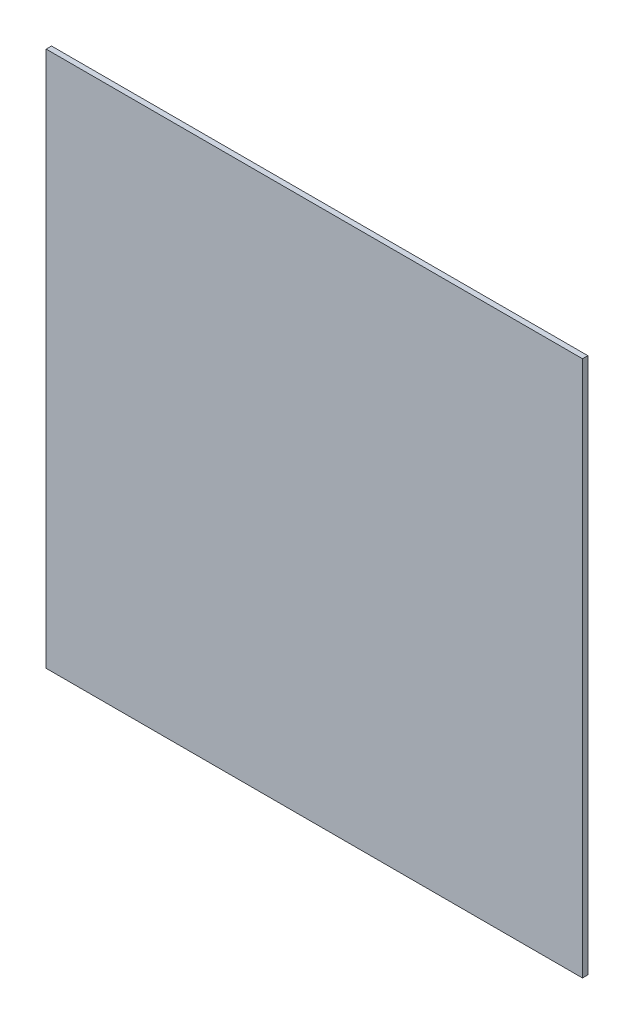
SolidWorks part; units mm, degrees
ref_plane "前视基准面" through (0, 0, 0) normal (0, 0, 1) x (1, 0, 0)
ref_plane "上视基准面" through (0, 0, 0) normal (0, 1, 0) x (1, 0, 0)
ref_plane "右视基准面" through (0, 0, 0) normal (1, 0, 0) x (0, 0, -1)
sketch "草图1" plane through (0, 0, 0) normal (0, 0, 1) x (1, 0, 0)
  line L1 (750, -750) -> (-750, -750)
  line L2 (750, -750) -> (750, 750)
  line L3 (750, 750) -> (-750, 750)
  line L4 (-750, -750) -> (-750, 750)
  line L5 (750, -750) -> (-750, 750) construction
  line L6 (750, 750) -> (-750, -750) construction
  point P0 (0, 0)
  dimension "D1" = 1500
  dimension "D2" = 1500
extrude "凸台-拉伸1" add sketch "草图1" along normal blind 15
